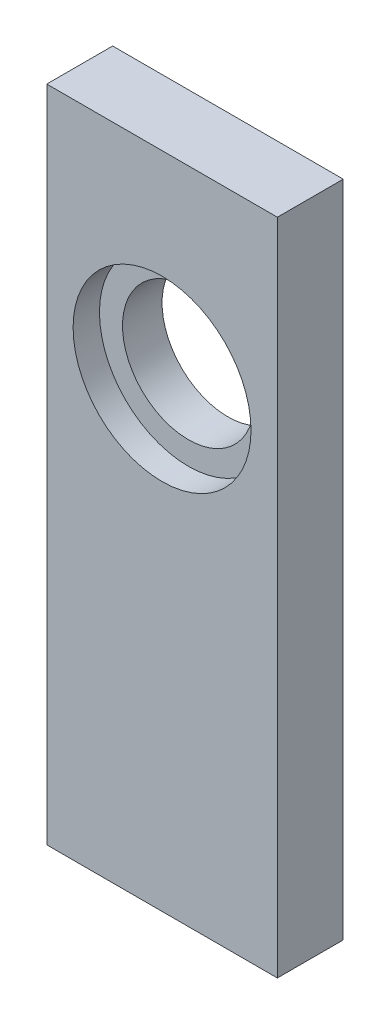
SolidWorks part; units mm, degrees
ref_plane "Front Plane" through (0, 0, 0) normal (0, 0, 1) x (1, 0, 0)
ref_plane "Top Plane" through (0, 0, 0) normal (0, 1, 0) x (1, 0, 0)
ref_plane "Right Plane" through (0, 0, 0) normal (1, 0, 0) x (0, 0, -1)
sketch "Sketch1" plane through (0, 0, 0) normal (0, 0, 1) x (1, 0, 0)
  line L0 (-17.5, 25) -> (-17.5, 75)
  line L1 (-17.5, -25) -> (17.5, -25)
  line L2 (-17.5, -25) -> (-17.5, 25)
  line L5 (-17.5, -25) -> (0, 0) construction
  line L6 (0, 0) -> (17.5, -25) construction
  line L7 (-17.5, 75) -> (17.5, 75)
  line L9 (17.5, 75) -> (17.5, -25)
  point P0 (0, 0)
  dimension "D1" = 100
  dimension "D2" = 35
extrude "Boss-Extrude1" add sketch "Sketch1" along normal blind 10
sketch "Sketch4" plane through (0, 0, 10) normal (0, 0, 1) x (1, 0, 0)
  line L0 (0, -25) -> (0, 45) construction
  line L2 (-17.5, -25) -> (17.5, -25) construction
  circle A1 centre (0, 45) radius 13.5
  dimension "D1" = 70
  dimension "D2" = 27
extrude "Cut-Extrude1" cut sketch "Sketch4" against normal blind 4
sketch "Sketch5" plane through (0, 0, 6) normal (0, 0, 1) x (1, 0, 0)
  circle A1 centre (0, 45) radius 10
  dimension "D1" = 20
extrude "Cut-Extrude2" cut sketch "Sketch5" against normal through all
